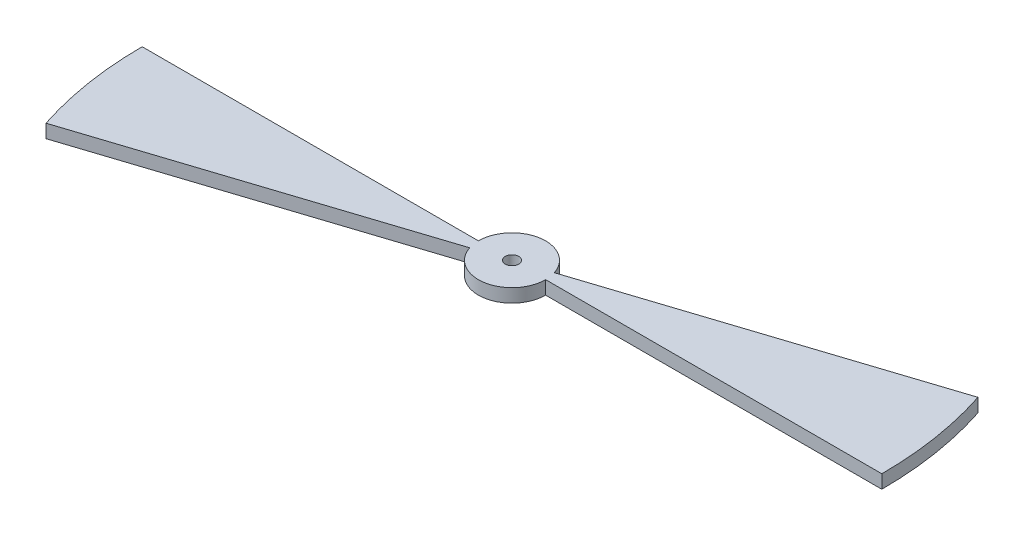
SolidWorks part; units mm, degrees
ref_plane "Front" through (0, 0, 0) normal (0, 0, 1) x (1, 0, 0)
ref_plane "Top" through (0, 0, 0) normal (0, 1, 0) x (1, 0, 0)
ref_plane "Right" through (0, 0, 0) normal (1, 0, 0) x (0, 0, -1)
sketch "草图1" plane through (0, 0, 0) normal (0, 1, 0) x (1, 0, 0)
  line L0 (2.5, 0) -> (27.5, 0)
  line L9 (-2.3776, -0.7725) -> (-26.1541, -8.498)
  line L10 (-2.5, 0) -> (-27.5, 0)
  line L19 (2.3776, 0.7725) -> (26.1541, 8.498)
  line L20 (-2.3776, 0.7725) -> (-26.1541, 8.498) [skipped]
  line L21 (-2.0225, 1.4695) -> (-22.248, 16.1641) [skipped]
  line L22 (-1.4695, 2.0225) -> (-16.1641, 22.248) [skipped]
  line L23 (-0.7725, 2.3776) -> (-8.498, 26.1541) [skipped]
  line L24 (0, 2.5) -> (0, 27.5) [skipped]
  line L25 (0.7725, 2.3776) -> (8.498, 26.1541) [skipped]
  line L26 (1.4695, 2.0225) -> (16.1641, 22.248) [skipped]
  line L27 (2.0225, 1.4695) -> (22.248, 16.1641) [skipped]
  line L28 (-2.0225, -1.4695) -> (-22.248, -16.1641) [skipped]
  line L29 (-1.4695, -2.0225) -> (-16.1641, -22.248) [skipped]
  line L30 (-0.7725, -2.3776) -> (-8.498, -26.1541) [skipped]
  line L31 (0, -2.5) -> (0, -27.5) [skipped]
  line L32 (0.7725, -2.3776) -> (8.498, -26.1541) [skipped]
  line L33 (1.4695, -2.0225) -> (16.1641, -22.248) [skipped]
  line L34 (2.0225, -1.4695) -> (22.248, -16.1641) [skipped]
  line L35 (2.3776, -0.7725) -> (26.1541, -8.498) [skipped]
  circle A0 centre (0, 0) radius 2.5
  circle A1 centre (0, 0) radius 0.5
  arc A2 (27.5, 0) -> (26.1541, 8.498) centre (0, 0) ccw
  arc A3 (-27.5, 0) -> (-26.1541, -8.498) centre (0, 0) ccw
  point P48 (0, 0)
  dimension "D1" = 5
  dimension "D2" = 1
  dimension "D3" = 55
  dimension "D4" = 20
extrude "凸台-拉伸1" add sketch "草图1" along normal blind 1 contours L10 A3 L9 A0 | L0 A2 L19 A0 | A0 A1
